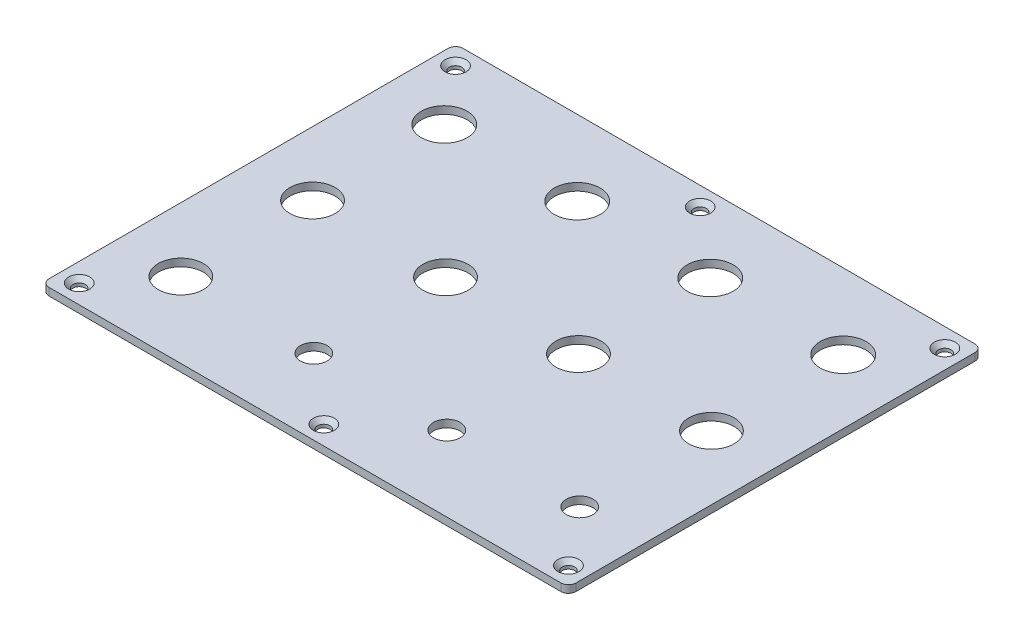
SolidWorks part; units mm, degrees
ref_plane "Front Plane" through (0, 0, 0) normal (0, 0, 1) x (1, 0, 0)
ref_plane "Top Plane" through (0, 0, 0) normal (0, 1, 0) x (1, 0, 0)
ref_plane "Right Plane" through (0, 0, 0) normal (1, 0, 0) x (0, 0, -1)
sketch "Bottom Plate" plane through (0, 0, 0) normal (0, 1, 0) x (1, 0, 0)
  line L1 (0, 0) -> (-140, 0)
  line L2 (0, 0) -> (0, 110)
  line L3 (0, 110) -> (-140, 110)
  line L4 (-140, 0) -> (-140, 110)
  dimension "D1" = 140
  dimension "D2" = 110
extrude "Bottom Plate EXT" add sketch "Bottom Plate" along normal blind 2
sketch "Middle Row" plane through (0, 2, 0) normal (0, 1, 0) x (1, 0, 0)
  line L0 (-140, 110) -> (-140, 0) construction
  line L1 (-140, 55) -> (0, 55) construction
  line L2 (0, 0) -> (0, 110) construction
  circle A0 centre (-123, 55) radius 6
  circle A1 centre (-87.6667, 55) radius 6
  circle A2 centre (-52.3333, 55) radius 6
  circle A3 centre (-17, 55) radius 6
  dimension "D1" = 12
  dimension "D2" = 35.3333
  dimension "D6" = 35.3333
  dimension "D3" = 35.3333
  dimension "D4" = 17
extrude "Middle Row Cut" cut sketch "Middle Row" against normal through all
sketch "Top Row" plane through (0, 2, 0) normal (0, 1, 0) x (1, 0, 0)
  line L0 (0, 0) -> (0, 110) construction
  line L1 (-140, 110) -> (-140, 0) construction
  line L2 (-123, 90) -> (-17, 90) construction
  line L3 (0, 110) -> (-140, 110) construction
  line L7 (-58.4333, 90) -> (-17, 90) construction
  circle A0 centre (-123, 90) radius 6.1
  circle A1 centre (-87.6667, 90) radius 6.1
  circle A2 centre (-52.3333, 90) radius 6.1
  circle A3 centre (-17, 90) radius 6.1
  dimension "D1" = 12.2
  dimension "D2" = 20
  dimension "D7" = 12.2
  dimension "D8" = 35.3333
  dimension "D3" = 17
  dimension "D4" = 35.3333
  dimension "D5" = 106
  dimension "D6" = 17
extrude "Top Row Cut" cut sketch "Top Row" against normal through all
sketch "Bottom Row" plane through (0, 2, 0) normal (0, 1, 0) x (1, 0, 0)
  line L0 (-140, 0) -> (0, 0) construction
  line L1 (-140, 110) -> (-140, 0) construction
  circle A0 centre (-87.6667, 20) radius 3.55
  circle A1 centre (-52.3333, 20) radius 3.55
  circle A2 centre (-17, 20) radius 3.55
  circle A5 centre (-123, 20) radius 6
  circle A6 centre (-123, 55) radius 6 construction
  dimension "D1" = 7.1
  dimension "D2" = 20
  dimension "D3" = 35.3333
  dimension "D4" = 35.3333
  dimension "D5" = 35.3333
  dimension "D6" = 17
extrude "Bottom Row Cut" cut sketch "Bottom Row" against normal through all
sketch "Plate Screws" plane through (0, 2, 0) normal (0, 1, 0) x (1, 0, 0)
  line L0 (0, 110) -> (-140, 110) construction
  line L1 (-140, 110) -> (-140, 0) construction
  line L2 (-140, 0) -> (0, 0) construction
  line L3 (0, 0) -> (0, 110) construction
  line L4 (-70, 110) -> (-70, 59.8221) construction
  line L5 (0, 55) -> (-30.2044, 55) construction
  circle A0 centre (-135, 105) radius 1.65
  circle A1 centre (-5, 105) radius 1.65
  circle A2 centre (-5, 5) radius 1.65
  circle A3 centre (-135, 5) radius 1.65
  circle A4 centre (-70, 105) radius 1.65
  circle A5 centre (-70, 5) radius 1.65
  dimension "D1" = 3.3
  dimension "D2" = 5
  dimension "D3" = 5
  dimension "D4" = 5
  dimension "D5" = 5
extrude "Plate Screws Cut" cut sketch "Plate Screws" against normal through all
sketch "Plate Screw Head" plane through (0, 2, 0) normal (0, 1, 0) x (1, 0, 0)
  line L0 (-70, 110) -> (-70, 73.7034) construction
  line L1 (0, 110) -> (-140, 110) construction
  line L2 (0, 55) -> (-52.6177, 55) construction
  line L3 (0, 0) -> (0, 110) construction
  circle A0 centre (-135, 105) radius 2.8
  circle A1 centre (-5, 105) radius 2.8
  circle A2 centre (-5, 5) radius 2.8
  circle A3 centre (-135, 5) radius 2.8
  circle A4 centre (-70, 105) radius 2.8
  circle A5 centre (-70, 5) radius 2.8
  dimension "D1" = 5.6
extrude "Plate Screw Head Cut" cut sketch "Plate Screw Head" against normal blind 2 draft 45
fillet "Fillet1" radius 2 1 edges at (-140, 1, -110)
fillet "Fillet2" radius 2 1 edges at (0, 1, -110)
fillet "Fillet3" radius 2 1 edges at (0, 1, 0)
fillet "Fillet4" radius 2 1 edges at (-140, 1, 0)
equation "\"SPACER_THIRD\"= \"D5@Top Row\" / 3mm"
equation "\"D4@Top Row\"=\"SPACER_THIRD\""
equation "\"D8@Top Row\"=\"SPACER_THIRD\""
equation "\"SPACER_SIDE\"= 17mm"
equation "\"D3@Top Row\" = \"SPACER_SIDE\""
equation "\"D6@Top Row\" = \"SPACER_SIDE\""
equation "\"D4@Middle Row\" = \"SPACER_SIDE\""
equation "\"D2@Middle Row\"=\"SPACER_THIRD\""
equation "\"D3@Middle Row\"=\"SPACER_THIRD\""
equation "\"D6@Middle Row\"=\"SPACER_THIRD\""
equation "\"D6@Bottom Row\" = \"SPACER_SIDE\""
equation "\"D5@Bottom Row\"=\"SPACER_THIRD\""
equation "\"D3@Bottom Row\"=\"SPACER_THIRD\""
equation "\"D4@Bottom Row\"=\"SPACER_THIRD\""
equation "\"SPACER_TOP\"= 20mm"
equation "\"D2@Top Row\"=\"SPACER_TOP\""
equation "\"D2@Bottom Row\"=\"SPACER_TOP\""
equation "\"BUTTON_METAL\"=16.5"
equation "\"BUTTON_PUSH\"=12.2"
equation "\"D1@Top Row\"=\"BUTTON_PUSH\""
equation "\"D7@Top Row\"=\"BUTTON_PUSH\""
